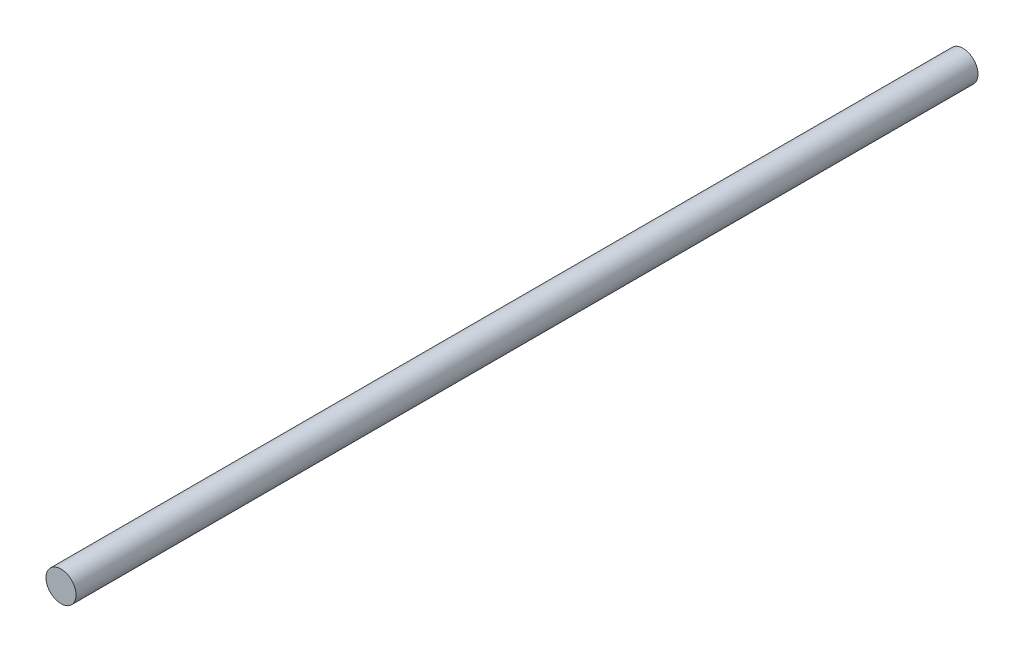
SolidWorks part; units mm, degrees
ref_plane "Plan de face" through (0, 0, 0) normal (0, 0, 1) x (1, 0, 0)
ref_plane "Plan de dessus" through (0, 0, 0) normal (0, 1, 0) x (1, 0, 0)
ref_plane "Plan de droite" through (0, 0, 0) normal (1, 0, 0) x (0, 0, -1)
sketch "Esquisse1" plane through (0, 0, 0) normal (0, 0, 1) x (1, 0, 0)
  circle A0 centre (0, 0) radius 10
  dimension "D1" = 20
extrude "Boss.-Extru.1" add sketch "Esquisse1" along normal blind 600
